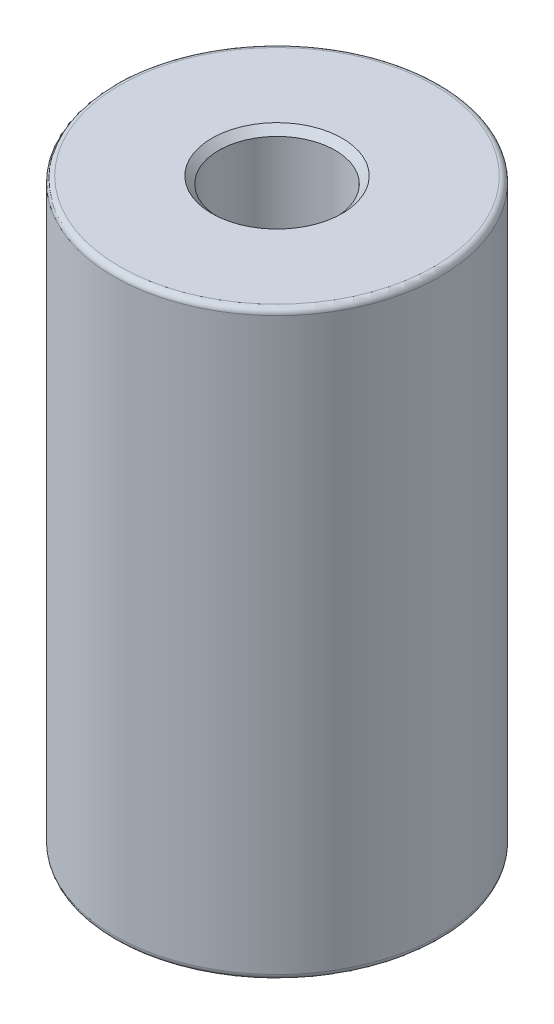
SolidWorks part; units mm, degrees
ref_plane "前视基准面" through (0, 0, 0) normal (0, 0, 1) x (1, 0, 0)
ref_plane "上视基准面" through (0, 0, 0) normal (0, 1, 0) x (1, 0, 0)
ref_plane "右视基准面" through (0, 0, 0) normal (1, 0, 0) x (0, 0, -1)
other "Configuration Table"
sketch "草图1" plane through (0, 0, 0) normal (0, 1, 0) x (1, 0, 0)
  circle A0 centre (0, 0) radius 7
  dimension "D1" = 14
extrude "凸台-拉伸1" add sketch "草图1" along normal blind 25
sketch "草图2" plane through (0, 0, 0) normal (0, 1, 0) x (1, 0, 0)
  circle A0 centre (0, 0) radius 2.5
  dimension "D1" = 5
extrude "切除-拉伸1" cut sketch "草图2" against normal blind 10 from surface at 25 starting at face at (0, 25, 7)
sketch "草图3" plane through (0, 0, 0) normal (0, 1, 0) x (1, 0, 0)
  circle A0 centre (0, 0) radius 4
  dimension "D1" = 8
extrude "切除-拉伸2" cut sketch "草图3" along normal blind 15
fillet "圆角1" radius 0.25 2 edges at (0, 0, 7) (0, 25, 7)
chamfer "倒角1" distance 0.3 angle 45 2 edges at (0, 0, 4) (0, 25, 2.5)
